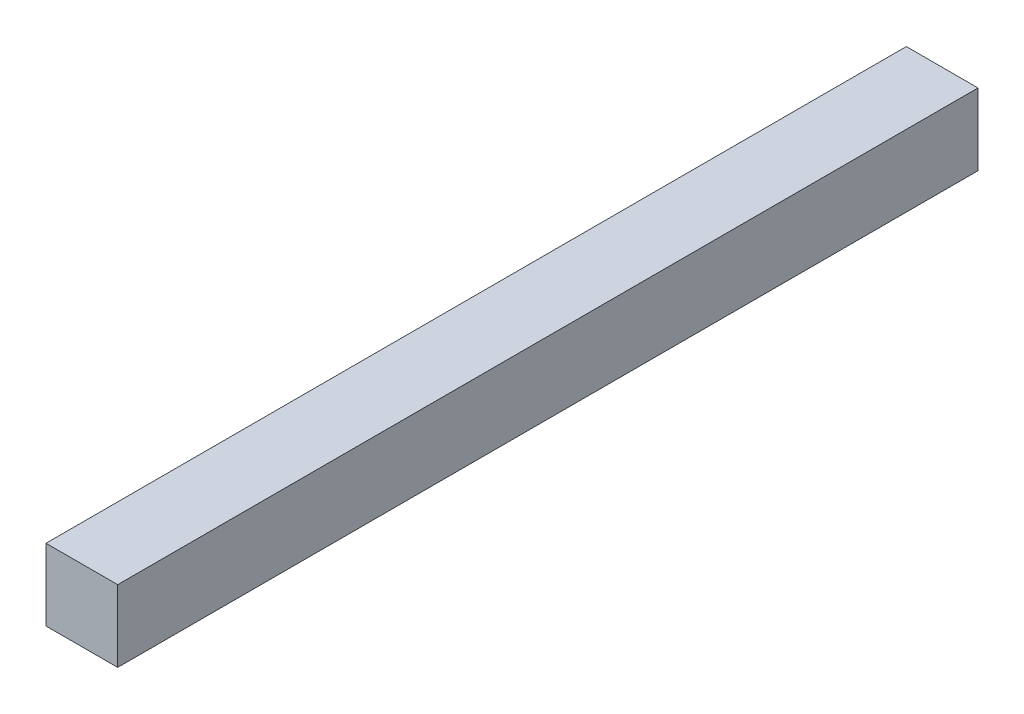
SolidWorks part; units mm, degrees
ref_plane "Front Plane" through (0, 0, 0) normal (0, 0, 1) x (1, 0, 0)
ref_plane "Top Plane" through (0, 0, 0) normal (0, 1, 0) x (1, 0, 0)
ref_plane "Right Plane" through (0, 0, 0) normal (1, 0, 0) x (0, 0, -1)
sketch "Sketch1" plane through (0, 0, 0) normal (0, 0, 1) x (1, 0, 0)
  line L1 (0, 0) -> (-3.175, 0)
  line L2 (0, 0) -> (0, 3.175)
  line L3 (0, 3.175) -> (-3.175, 3.175)
  line L4 (-3.175, 0) -> (-3.175, 3.175)
extrude "Boss-Extrude1" add sketch "Sketch1" along normal blind 38.1
